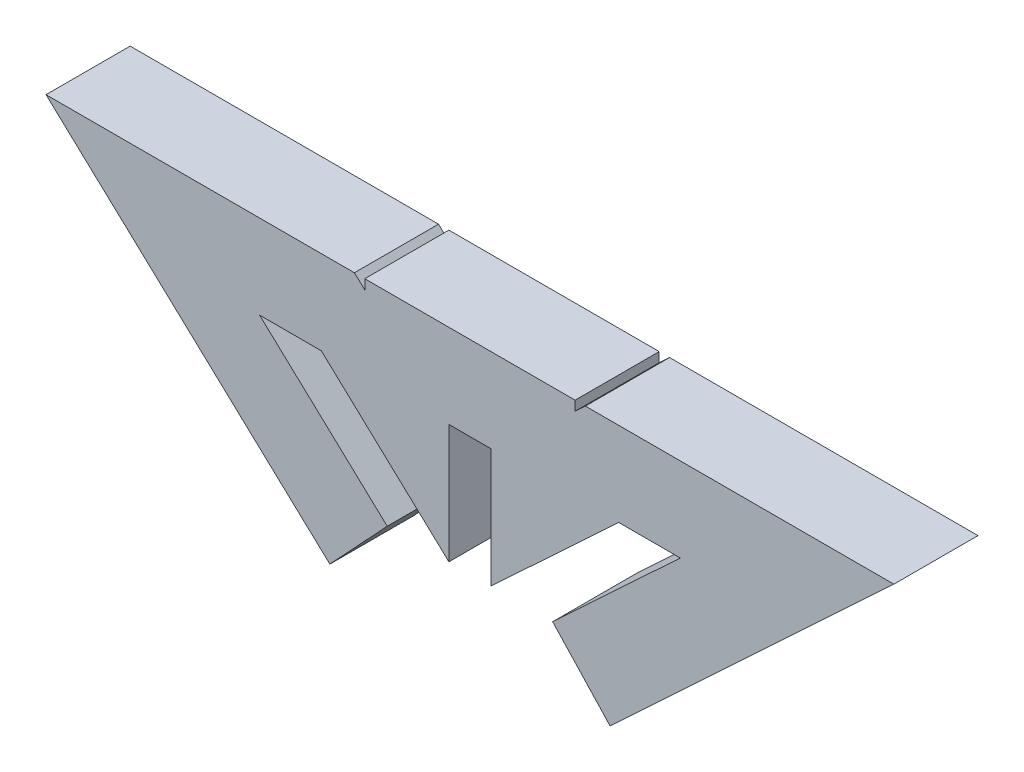
SolidWorks part; units mm, degrees
ref_plane "正面" through (0, 0, 0) normal (0, 0, 1) x (1, 0, 0)
ref_plane "平面" through (0, 0, 0) normal (0, 1, 0) x (1, 0, 0)
ref_plane "右側面" through (0, 0, 0) normal (1, 0, 0) x (0, 0, -1)
sketch "ｽｹｯﾁ1" plane through (0, 0, 0) normal (0, 0, 1) x (1, 0, 0)
  line L0 (-2.5, 0) -> (2.5, 0)
  line L1 (2.5, 0) -> (2.5, -14.1431)
  line L2 (-2.5, 0) -> (-2.5, -14.1431)
  line L3 (2.5, -14.1431) -> (17.6682, 0)
  line L4 (17.6682, 0) -> (25, 0)
  line L5 (25, 0) -> (9.8318, -14.1431)
  line L6 (-2.5, -14.1431) -> (-17.6682, 0)
  line L7 (-17.6682, 0) -> (-25, 0)
  line L8 (-25, 0) -> (-9.8318, -14.1431)
  point P9 (0, 0)
  point P14 (8.7929, 0.4273)
  dimension "D1" = 5
  dimension "D2" = 5
  dimension "D3" = 5
  dimension "D4" = 25
  dimension "D5" = 25
extrude "押し出し-薄板1" add sketch "ｽｹｯﾁ1" along normal blind 10 thin thin type one direction wall 10
